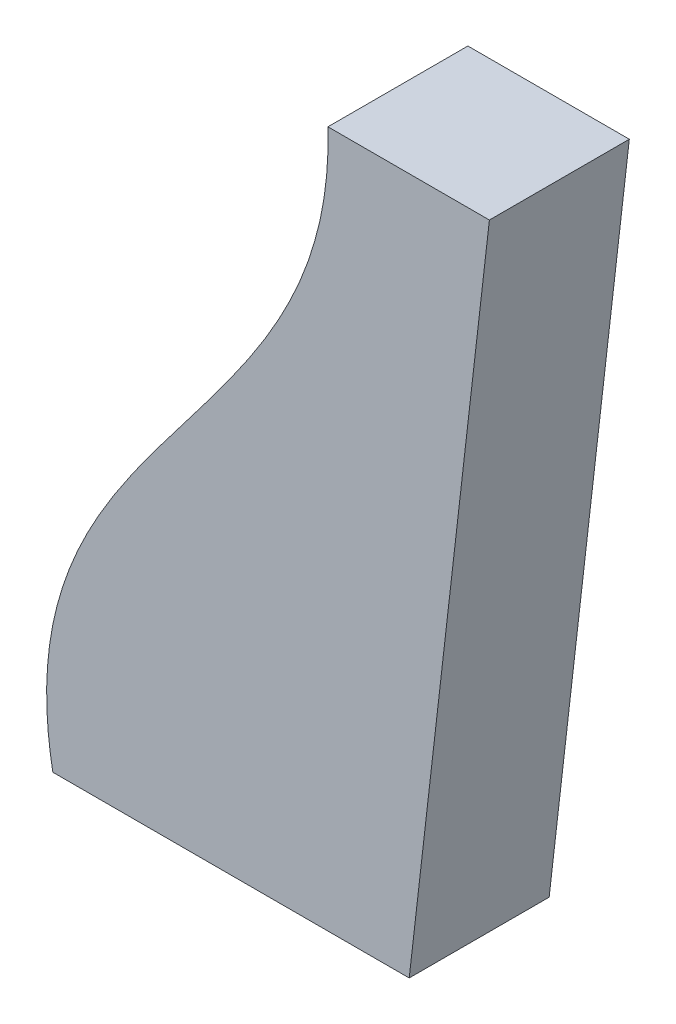
SolidWorks part; units mm, degrees
ref_plane "Front Plane" through (0, 0, 0) normal (0, 0, 1) x (1, 0, 0)
ref_plane "Top Plane" through (0, 0, 0) normal (0, 1, 0) x (1, 0, 0)
ref_plane "Right Plane" through (0, 0, 0) normal (1, 0, 0) x (0, 0, -1)
sketch "Sketch1" plane through (0, 0, 0) normal (0, 0, 1) x (1, 0, 0)
  line L0 (11.7954, 29.8643) -> (18.7179, 29.8643)
  line L1 (18.7179, 29.8643) -> (15.28, 0)
  line L2 (15.28, 0) -> (0, 0)
  spline S0 degree 3 poles (0, 0) (-2.3952, 12.814) (12.1786, 17.6112) (11.7954, 29.8643) knots 0 0 0 0 1 1 1 1
extrude "Boss-Extrude1" add sketch "Sketch1" along normal blind 6
